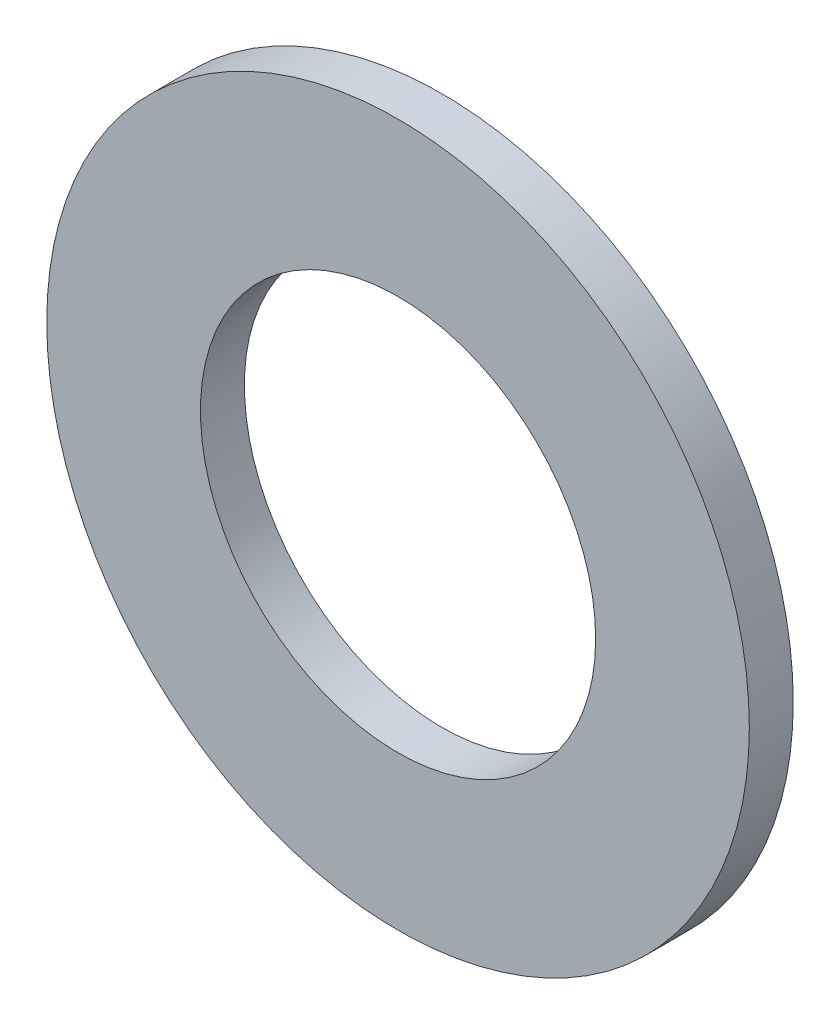
SolidWorks part; units mm, degrees
material "Латунь"
ref_plane "Спереди" through (0, 0, 0) normal (0, 0, 1) x (1, 0, 0)
ref_plane "Сверху" through (0, 0, 0) normal (0, 1, 0) x (1, 0, 0)
ref_plane "Справа" through (0, 0, 0) normal (1, 0, 0) x (0, 0, -1)
sketch "Эскиз1" plane through (0, 0, 0) normal (0, 0, 1) x (1, 0, 0)
  circle A0 centre (0, 0) radius 8
  circle A1 centre (0, 0) radius 4.5
  point P3 (0, 0)
  dimension "D1" = 9
  dimension "D2" = 16
extrude "Бобышка-Вытянуть1" add sketch "Эскиз1" along normal blind 1
equation "\"Внутренний диаметр\" = 8  '!!!"
equation "\"Внешний диаметр\" = 16"
equation "\"Толщина\" = 1  'Толщина шайбы между пластиной прижима и несущей пластиной"
equation "\"D1@Эскиз1\"=\"Внутренний диаметр\"+1"
equation "\"D1@Бобышка-Вытянуть1\"=\"Толщина\""
equation "\"D2@Эскиз1\"=\"Внешний диаметр\""
